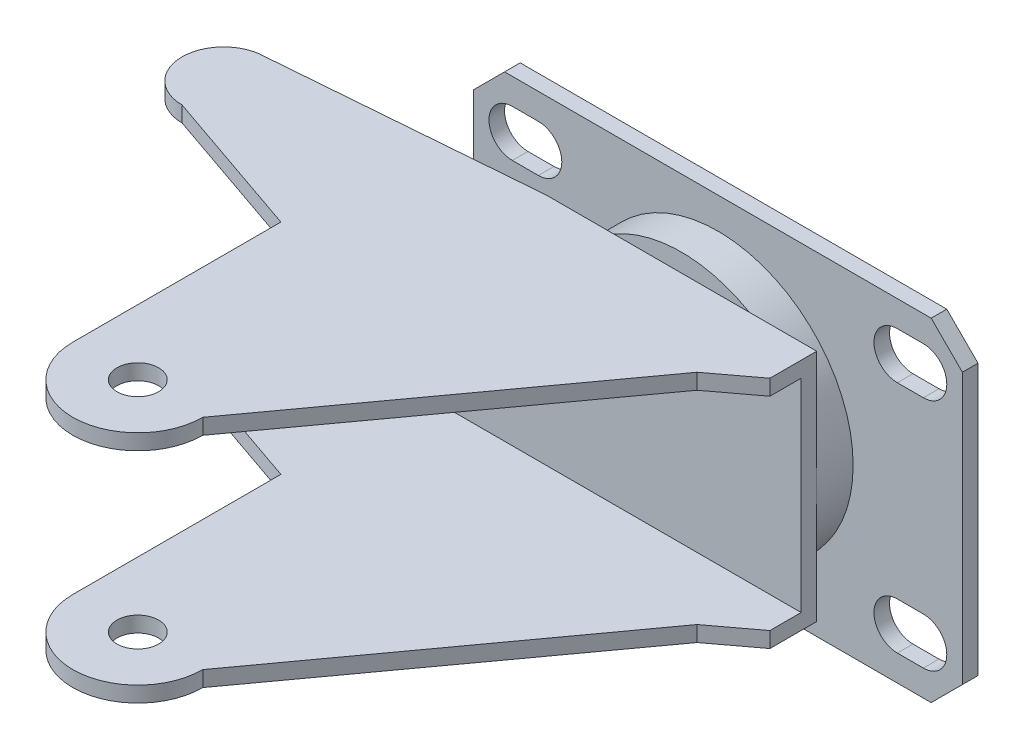
SolidWorks part; units mm, degrees
ref_plane "Plan de face" through (0, 0, 0) normal (0, 0, 1) x (1, 0, 0)
ref_plane "Plan de dessus" through (0, 0, 0) normal (0, 1, 0) x (1, 0, 0)
ref_plane "Plan de droite" through (0, 0, 0) normal (1, 0, 0) x (0, 0, -1)
sketch "Esquisse1" plane through (0, 0, 0) normal (0, 0, 1) x (1, 0, 0)
  line L1 (0, 0) -> (94, 0)
  line L2 (0, 0) -> (0, 64)
  line L3 (0, 64) -> (94, 64)
  line L4 (94, 0) -> (94, 64)
  dimension "D1" = 94
  dimension "D2" = 64
extrude "Boss.-Extru.1" add sketch "Esquisse1" along normal blind 3
sketch "Esquisse2" plane through (0, 0, 3) normal (0, 0, 1) x (1, 0, 0)
  line L0 (47, 0) -> (47, 64) construction
  line L1 (0, 0) -> (94, 0) construction
  line L2 (94, 64) -> (0, 64) construction
  circle A0 centre (47, 32) radius 26
  dimension "D1" = 52
extrude "Boss.-Extru.2" add sketch "Esquisse2" along normal blind 7
ref_point "Point1"
ref_plane "Plan2" through (0, 32, 0) normal (0, 1, 0) x (1, 0, 0)
sketch "Esquisse3" plane through (0, 32, 0) normal (0, 1, 0) x (1, 0, 0)
  line L0 (73, -10) -> (73, -19)
  line L1 (73, -19) -> (65, -25)
  line L2 (65, -25) -> (25, -80)
  line L3 (0, -80) -> (0, -40)
  line L4 (0, -40) -> (-29, -30)
  line L5 (-29, -14) -> (21, -10)
  line L6 (-29, -30) -> (-29, -14) construction
  line L7 (73, -10) -> (21, -10)
  line L8 (0, -80) -> (12.5, -80) construction
  line L9 (12.5, -80) -> (25, -80) construction
  line L10 (21, -10) -> (73, -10) construction
  line L11 (0, -3) -> (94, -3) construction
  arc A0 (25, -80) -> (0, -80) centre (12.5, -80) cw
  arc A1 (-29, -30) -> (-29, -14) centre (-29, -22) cw
  point P16 (47, -3)
  dimension "D1" = 50
  dimension "D2" = 70
  dimension "D3" = 25
  dimension "D4" = 9
  dimension "D5" = 6
  dimension "D6" = 8
  dimension "D7" = 40
  dimension "D8" = 40
  dimension "D9" = 10
  dimension "D10" = 16
extrude "Boss.-Extru.3" add sketch "Esquisse3" along normal blind 22.5 and the other way blind 22.5
sketch "Esquisse4" plane through (94, 0, 0) normal (1, 0, 0) x (0, 0, -1)
  line L0 (0, 32) -> (-99, 32) construction
  line L1 (0, 0) -> (0, 64) construction
  line L2 (-99, 12.5) -> (-99, 51.5)
  line L3 (-99, 51.5) -> (-13, 51.5)
  line L4 (-13, 51.5) -> (-13, 12.5)
  line L5 (-80, 54.5) -> (-25, 54.5) construction
  line L6 (-99, 12.5) -> (-13, 12.5)
  point P10 (-13, 32)
  dimension "D1" = 13
  dimension "D2" = 99
  dimension "D3" = 3
extrude "Enlèv. mat.-Extru.1" cut sketch "Esquisse4" against normal through all both and the other way through all
sketch "Esquisse5" plane through (0, 9.5, 0) normal (0, -1, 0) x (1, 0, 0)
  circle A0 centre (12.5, 80) radius 4
  dimension "D1" = 8
extrude "Enlèv. mat.-Extru.2" cut sketch "Esquisse5" against normal through all both and the other way through all
sketch "Esquisse6" plane through (0, 0, 0) normal (0, 0, -1) x (-1, 0, 0)
  line L0 (-94, 32) -> (-47, 32) construction
  line L1 (-94, 0) -> (-94, 64) construction
  line L2 (-47, 32) -> (-47, 64) construction
  line L3 (-94, 64) -> (0, 64) construction
  line L4 (-86.5, 54.5) -> (-81.5, 54.5) construction
  line L5 (-86.5, 59) -> (-81.5, 59)
  line L6 (-86.5, 50) -> (-81.5, 50)
  line L7 (-7.5, 54.5) -> (-12.5, 54.5) construction
  line L8 (-7.5, 59) -> (-12.5, 59)
  line L9 (-7.5, 50) -> (-12.5, 50)
  line L10 (-7.5, 9.5) -> (-12.5, 9.5) construction
  line L11 (-7.5, 5) -> (-12.5, 5)
  line L12 (-7.5, 14) -> (-12.5, 14)
  line L13 (-86.5, 9.5) -> (-81.5, 9.5) construction
  line L14 (-86.5, 5) -> (-81.5, 5)
  line L15 (-86.5, 14) -> (-81.5, 14)
  arc A0 (-86.5, 59) -> (-86.5, 50) centre (-86.5, 54.5) ccw
  arc A1 (-81.5, 50) -> (-81.5, 59) centre (-81.5, 54.5) ccw
  arc A2 (-7.5, 59) -> (-7.5, 50) centre (-7.5, 54.5) cw
  arc A3 (-12.5, 50) -> (-12.5, 59) centre (-12.5, 54.5) cw
  arc A4 (-7.5, 5) -> (-7.5, 14) centre (-7.5, 9.5) ccw
  arc A5 (-12.5, 14) -> (-12.5, 5) centre (-12.5, 9.5) ccw
  arc A6 (-86.5, 5) -> (-86.5, 14) centre (-86.5, 9.5) cw
  arc A7 (-81.5, 14) -> (-81.5, 5) centre (-81.5, 9.5) cw
  point P9 (-84, 54.5)
  point P16 (-10, 54.5)
  point P23 (-10, 9.5)
  point P30 (-84, 9.5)
  dimension "D1" = 9
  dimension "D2" = 5
  dimension "D3" = 22.5
  dimension "D4" = 37
extrude "Enlèv. mat.-Extru.3" cut sketch "Esquisse6" against normal up to vertex (3 mm away) up to point (94, 64, 3)
chamfer "Chanfrein1" distance 6 angle 45 4 edges at (94, 0, 1.5) (0, 0, 1.5) (0, 64, 1.5) (94, 64, 1.5)
